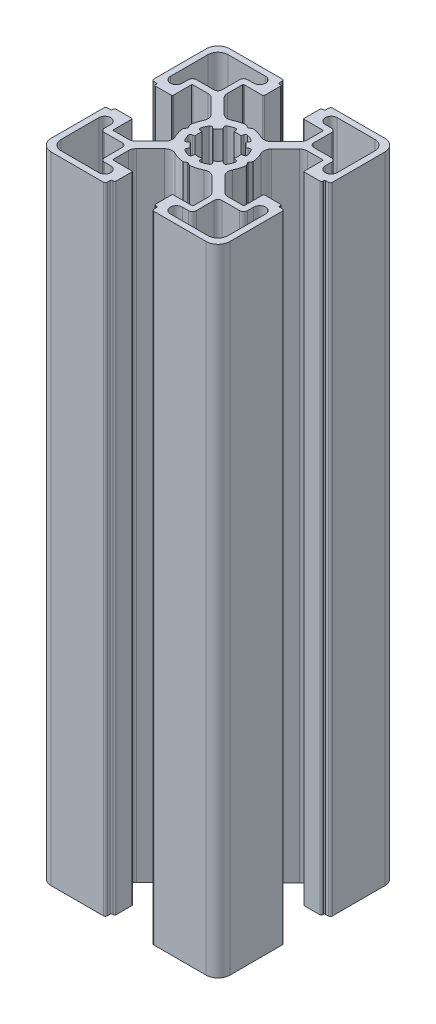
SolidWorks part; units mm, degrees
ref_plane "Front Plane" through (0, 0, 0) normal (0, 0, 1) x (1, 0, 0)
ref_plane "Top Plane" through (0, 0, 0) normal (0, 1, 0) x (1, 0, 0)
ref_plane "Right Plane" through (0, 0, 0) normal (1, 0, 0) x (0, 0, -1)
sketch "Sketch1" plane through (0, 0, 0) normal (0, 1, 0) x (1, 0, 0)
  line L106 (-18, 9.0002) -> (-18, 10.55)
  line L107 (-21, 18.5) -> (-21, 9.0002)
  line L108 (-9, 21) -> (-18.5, 21)
  line L109 (-10.55, 18) -> (-9, 18)
  line L110 (0.9675, 5.4811) -> (0.8674, 4.9242)
  line L111 (2.864, 4.0985) -> (3.1913, 4.5626)
  line L112 (4.5668, 3.2081) -> (4.0897, 2.8765)
  line L113 (4.9205, 0.8878) -> (5.4897, 0.9862)
  line L114 (5.4898, -0.9862) -> (4.9205, -0.8878)
  line L115 (4.0897, -2.8765) -> (4.5668, -3.2082)
  line L116 (3.1914, -4.5627) -> (2.864, -4.0985)
  line L117 (0.8674, -4.9242) -> (0.9675, -5.4811)
  line L118 (-0.9675, -5.4811) -> (-0.8674, -4.9242)
  line L119 (-2.864, -4.0985) -> (-3.1913, -4.5626)
  line L120 (-4.5668, -3.2082) -> (-4.0897, -2.8765)
  line L121 (-4.9205, -0.8878) -> (-5.4897, -0.9862)
  line L122 (-5.4899, 0.9862) -> (-4.9205, 0.8878)
  line L123 (-4.0897, 2.8765) -> (-4.5668, 3.2081)
  line L124 (-3.1914, 4.5627) -> (-2.864, 4.0985)
  line L125 (-0.8674, 4.9242) -> (-0.9675, 5.4811)
  line L126 (-11.55, 12.55) -> (-11.55, 17)
  line L127 (-17, 11.55) -> (-12.55, 11.55)
  line L128 (-21, -9.0002) -> (-21, -18.5)
  line L129 (-18, -10.55) -> (-18, -9.0002)
  line L130 (-12.55, -11.55) -> (-17, -11.55)
  line L131 (-11.55, -17) -> (-11.55, -12.55)
  line L132 (-9, -18) -> (-10.55, -18)
  line L133 (-18.5, -21) -> (-9, -21)
  line L134 (21, 9.0002) -> (21, 18.5)
  line L135 (18, 10.55) -> (18, 9.0002)
  line L136 (12.55, 11.55) -> (17, 11.55)
  line L137 (11.55, 17) -> (11.55, 12.55)
  line L138 (9, 18) -> (10.55, 18)
  line L139 (18.5, 21) -> (9, 21)
  line L140 (17, -11.55) -> (12.55, -11.55)
  line L141 (18, -9.0002) -> (18, -10.55)
  line L142 (21, -18.5) -> (21, -9.0002)
  line L143 (9, -21) -> (18.5, -21)
  line L144 (10.55, -18) -> (9, -18)
  line L145 (11.55, -12.55) -> (11.55, -17)
  line L146 (7.5635, 5.8587) -> (11.1298, 9.425)
  line L147 (12.5048, 9.9945) -> (16.3169, 9.9945)
  line L148 (16.5169, 9.7945) -> (16.5169, 5.2)
  line L149 (16.7169, 5) -> (20.7196, 5)
  line L150 (21.0196, 5.3) -> (21.0196, 5.5)
  line L151 (21.3196, 5.8) -> (22, 5.8)
  line L152 (22.5, 6.3) -> (22.5, 19.5)
  line L153 (19.5, 22.5) -> (6.3757, 22.5)
  line L154 (5.8757, 22) -> (5.8757, 21.3)
  line L155 (5.5757, 21) -> (5.3, 21)
  line L156 (5, 20.7) -> (5, 16.6668)
  line L157 (5.2, 16.4668) -> (9.9054, 16.4668)
  line L158 (10.1054, 16.2668) -> (10.1054, 12.4716)
  line L159 (9.5196, 11.0574) -> (5.9449, 7.4827)
  line L160 (0.7548, 7.9748) -> (0.1126, 7.6069)
  line L161 (-0.1126, 7.6069) -> (-0.7547, 7.9748)
  line L162 (-5.9449, 7.4827) -> (-9.5196, 11.0574)
  line L163 (-10.1054, 12.4716) -> (-10.1054, 16.2668)
  line L164 (-9.9054, 16.4668) -> (-5.2, 16.4668)
  line L165 (-5, 16.6668) -> (-5, 20.7)
  line L166 (-5.3, 21) -> (-5.5757, 21)
  line L167 (-5.8757, 21.3) -> (-5.8757, 22)
  line L168 (-6.3757, 22.5) -> (-19.5, 22.5)
  line L169 (-22.5, 19.5) -> (-22.5, 6.3)
  line L170 (-22, 5.8) -> (-21.3196, 5.8)
  line L171 (-21.0196, 5.5) -> (-21.0196, 5.3)
  line L172 (-20.7196, 5) -> (-16.7169, 5)
  line L173 (-16.5169, 5.2) -> (-16.5169, 9.7945)
  line L174 (-16.3169, 9.9945) -> (-12.5048, 9.9945)
  line L175 (-11.1298, 9.425) -> (-7.5635, 5.8587)
  line L176 (-7.974, 0.7926) -> (-7.5401, 0.0468)
  line L177 (-7.5401, -0.0468) -> (-7.974, -0.7926)
  line L178 (-7.5635, -5.8587) -> (-11.1298, -9.425)
  line L179 (-12.5048, -9.9945) -> (-16.3169, -9.9945)
  line L180 (-16.5169, -9.7945) -> (-16.5169, -5.2)
  line L181 (-16.7169, -5) -> (-20.7196, -5)
  line L182 (-21.0196, -5.3) -> (-21.0196, -5.5)
  line L183 (-21.3196, -5.8) -> (-22, -5.8)
  line L184 (-22.5, -6.3) -> (-22.5, -19.5)
  line L185 (-19.5, -22.5) -> (-6.3757, -22.5)
  line L186 (-5.8757, -22) -> (-5.8757, -21.3)
  line L187 (-5.5757, -21) -> (-5.3, -21)
  line L188 (-5, -20.7) -> (-5, -16.6668)
  line L189 (-5.2, -16.4668) -> (-9.9054, -16.4668)
  line L190 (-10.1054, -16.2668) -> (-10.1054, -12.4716)
  line L191 (-9.5196, -11.0574) -> (-5.9449, -7.4827)
  line L192 (-0.7547, -7.9748) -> (-0.1126, -7.6069)
  line L193 (0.1126, -7.6069) -> (0.7548, -7.9748)
  line L194 (5.9449, -7.4827) -> (9.5196, -11.0574)
  line L195 (10.1054, -12.4716) -> (10.1054, -16.2668)
  line L196 (9.9054, -16.4668) -> (5.2, -16.4668)
  line L197 (5, -16.6668) -> (5, -20.7)
  line L198 (5.3, -21) -> (5.5757, -21)
  line L199 (5.8757, -21.3) -> (5.8757, -22)
  line L200 (6.3757, -22.5) -> (19.5, -22.5)
  line L201 (22.5, -19.5) -> (22.5, -6.3)
  line L202 (22, -5.8) -> (21.3196, -5.8)
  line L203 (21.0196, -5.5) -> (21.0196, -5.3)
  line L204 (20.7196, -5) -> (16.7169, -5)
  line L205 (16.5169, -5.2) -> (16.5169, -9.7945)
  line L206 (16.3169, -9.9945) -> (12.5048, -9.9945)
  line L207 (11.1298, -9.425) -> (7.5635, -5.8587)
  line L208 (7.974, -0.7926) -> (7.5401, -0.0468)
  line L209 (7.5401, 0.0468) -> (7.974, 0.7926)
  arc A140 (-17, 11.55) -> (-18, 10.55) centre (-17, 10.55) ccw
  arc A141 (-21, 9.0002) -> (-18, 9.0002) centre (-19.5, 9.0002) ccw
  arc A142 (-18.5, 21) -> (-21, 18.5) centre (-18.5, 18.5) ccw
  arc A143 (-9, 18) -> (-9, 21) centre (-9, 19.5) ccw
  arc A144 (-10.55, 18) -> (-11.55, 17) centre (-10.55, 17) ccw
  arc A145 (-12.55, 11.55) -> (-11.55, 12.55) centre (-12.55, 12.55) ccw
  arc A146 (-21, -18.5) -> (-18.5, -21) centre (-18.5, -18.5) ccw
  arc A147 (-18, -9.0002) -> (-21, -9.0002) centre (-19.5, -9.0002) ccw
  arc A148 (-18, -10.55) -> (-17, -11.55) centre (-17, -10.55) ccw
  arc A149 (-11.55, -12.55) -> (-12.55, -11.55) centre (-12.55, -12.55) ccw
  arc A150 (-11.55, -17) -> (-10.55, -18) centre (-10.55, -17) ccw
  arc A151 (-9, -21) -> (-9, -18) centre (-9, -19.5) ccw
  arc A152 (0.8674, 4.9242) -> (-0.8674, 4.9242) centre (0, 0) ccw
  arc A153 (1.5951, 5.8941) -> (0.9675, 5.4811) centre (1.4627, 5.4119) ccw
  arc A154 (3.0417, 5.301) -> (1.5951, 5.8941) centre (0.0235, 0) ccw
  arc A155 (3.1913, 4.5626) -> (3.0417, 5.301) centre (2.7943, 4.8665) ccw
  arc A156 (4.0897, 2.8765) -> (2.864, 4.0985) centre (0, 0) ccw
  arc A157 (5.3025, 3.0565) -> (4.5668, 3.2081) centre (4.868, 2.8091) ccw
  arc A158 (5.906, 1.6142) -> (5.3025, 3.0565) centre (0.0235, 0) ccw
  arc A159 (5.4897, 0.9862) -> (5.906, 1.6142) centre (5.4239, 1.4819) ccw
  arc A160 (4.9205, -0.8878) -> (4.9205, 0.8878) centre (0, 0) ccw
  arc A161 (5.906, -1.6142) -> (5.4898, -0.9862) centre (5.4239, -1.4819) ccw
  arc A162 (5.3025, -3.0564) -> (5.906, -1.6142) centre (0.0235, 0) ccw
  arc A163 (4.5668, -3.2082) -> (5.3025, -3.0564) centre (4.868, -2.8091) ccw
  arc A164 (2.864, -4.0985) -> (4.0897, -2.8765) centre (0, 0) ccw
  arc A165 (3.0416, -5.301) -> (3.1914, -4.5627) centre (2.7943, -4.8665) ccw
  arc A166 (1.5951, -5.8941) -> (3.0416, -5.301) centre (0.0235, 0) ccw
  arc A167 (0.9675, -5.4811) -> (1.5951, -5.8941) centre (1.4627, -5.4119) ccw
  arc A168 (-0.8674, -4.9242) -> (0.8674, -4.9242) centre (0, 0) ccw
  arc A169 (-1.5951, -5.8941) -> (-0.9675, -5.4811) centre (-1.4627, -5.4119) ccw
  arc A170 (-3.0416, -5.301) -> (-1.5951, -5.8941) centre (-0.0235, 0) ccw
  arc A171 (-3.1913, -4.5626) -> (-3.0416, -5.301) centre (-2.7943, -4.8665) ccw
  arc A172 (-4.0897, -2.8765) -> (-2.864, -4.0985) centre (0, 0) ccw
  arc A173 (-5.3025, -3.0565) -> (-4.5668, -3.2082) centre (-4.868, -2.8091) ccw
  arc A174 (-5.906, -1.6142) -> (-5.3025, -3.0565) centre (-0.0235, 0) ccw
  arc A175 (-5.4897, -0.9862) -> (-5.906, -1.6142) centre (-5.4239, -1.4819) ccw
  arc A176 (-4.9205, 0.8878) -> (-4.9205, -0.8878) centre (0, 0) ccw
  arc A177 (-5.906, 1.6141) -> (-5.4899, 0.9862) centre (-5.4239, 1.4818) ccw
  arc A178 (-5.3025, 3.0564) -> (-5.906, 1.6141) centre (-0.0235, 0) ccw
  arc A179 (-4.5668, 3.2081) -> (-5.3025, 3.0564) centre (-4.868, 2.8091) ccw
  arc A180 (-2.864, 4.0985) -> (-4.0897, 2.8765) centre (0, 0) ccw
  arc A181 (-3.0417, 5.301) -> (-3.1914, 4.5627) centre (-2.7943, 4.8665) ccw
  arc A182 (-1.5951, 5.8941) -> (-3.0417, 5.301) centre (-0.0235, 0) ccw
  arc A183 (-0.9675, 5.4811) -> (-1.5951, 5.8941) centre (-1.4627, 5.4119) ccw
  arc A184 (21, 18.5) -> (18.5, 21) centre (18.5, 18.5) ccw
  arc A185 (18, 9.0002) -> (21, 9.0002) centre (19.5, 9.0002) ccw
  arc A186 (18, 10.55) -> (17, 11.55) centre (17, 10.55) ccw
  arc A187 (11.55, 12.55) -> (12.55, 11.55) centre (12.55, 12.55) ccw
  arc A188 (11.55, 17) -> (10.55, 18) centre (10.55, 17) ccw
  arc A189 (9, 21) -> (9, 18) centre (9, 19.5) ccw
  arc A190 (12.55, -11.55) -> (11.55, -12.55) centre (12.55, -12.55) ccw
  arc A191 (17, -11.55) -> (18, -10.55) centre (17, -10.55) ccw
  arc A192 (21, -9.0002) -> (18, -9.0002) centre (19.5, -9.0002) ccw
  arc A193 (18.5, -21) -> (21, -18.5) centre (18.5, -18.5) ccw
  arc A194 (9, -18) -> (9, -21) centre (9, -19.5) ccw
  arc A195 (10.55, -18) -> (11.55, -17) centre (10.55, -17) ccw
  arc A196 (7.9999, 0.9154) -> (7.2004, 3.6119) centre (0.0496, 0.0249) ccw
  arc A197 (7.5635, 5.8587) -> (7.2004, 3.6119) centre (8.9385, 4.4837) ccw
  arc A198 (12.5048, 9.9945) -> (11.1298, 9.425) centre (12.5048, 8.05) ccw
  arc A199 (16.5169, 9.7945) -> (16.3169, 9.9945) centre (16.3169, 9.7945) ccw
  arc A200 (16.5169, 5.2) -> (16.7169, 5) centre (16.7169, 5.2) ccw
  arc A201 (20.7196, 5) -> (21.0196, 5.3) centre (20.7196, 5.3) ccw
  arc A202 (21.3196, 5.8) -> (21.0196, 5.5) centre (21.3196, 5.5) ccw
  arc A203 (22, 5.8) -> (22.5, 6.3) centre (22, 6.3) ccw
  arc A204 (22.5, 19.5) -> (19.5, 22.5) centre (19.5, 19.5) ccw
  arc A205 (6.3757, 22.5) -> (5.8757, 22) centre (6.3757, 22) ccw
  arc A206 (5.5757, 21) -> (5.8757, 21.3) centre (5.5757, 21.3) ccw
  arc A207 (5.3, 21) -> (5, 20.7) centre (5.3, 20.7) ccw
  arc A208 (5, 16.6668) -> (5.2, 16.4668) centre (5.2, 16.6668) ccw
  arc A209 (10.1054, 16.2668) -> (9.9054, 16.4668) centre (9.9054, 16.2668) ccw
  arc A210 (9.5196, 11.0574) -> (10.1054, 12.4716) centre (8.1054, 12.4716) ccw
  arc A211 (3.6665, 7.1733) -> (5.9449, 7.4827) centre (4.5855, 8.9496) ccw
  arc A212 (3.6665, 7.1733) -> (0.8753, 8.0001) centre (0.0235, 0) ccw
  arc A213 (0.8753, 8.0001) -> (0.7548, 7.9748) centre (0.8542, 7.8013) ccw
  arc A214 (0, 7.531) -> (0.1126, 7.6069) centre (-0.0489, 7.7249) ccw
  arc A215 (-0.1126, 7.6069) -> (0, 7.531) centre (0.0489, 7.7249) ccw
  arc A216 (-0.7547, 7.9748) -> (-0.8753, 8.0001) centre (-0.8542, 7.8013) ccw
  arc A217 (-0.8753, 8.0001) -> (-3.6665, 7.1733) centre (-0.0235, 0) ccw
  arc A218 (-5.9449, 7.4827) -> (-3.6665, 7.1733) centre (-4.5855, 8.9496) ccw
  arc A219 (-10.1054, 12.4716) -> (-9.5196, 11.0574) centre (-8.1054, 12.4716) ccw
  arc A220 (-9.9054, 16.4668) -> (-10.1054, 16.2668) centre (-9.9054, 16.2668) ccw
  arc A221 (-5.2, 16.4668) -> (-5, 16.6668) centre (-5.2, 16.6668) ccw
  arc A222 (-5, 20.7) -> (-5.3, 21) centre (-5.3, 20.7) ccw
  arc A223 (-5.8757, 21.3) -> (-5.5757, 21) centre (-5.5757, 21.3) ccw
  arc A224 (-5.8757, 22) -> (-6.3757, 22.5) centre (-6.3757, 22) ccw
  arc A225 (-19.5, 22.5) -> (-22.5, 19.5) centre (-19.5, 19.5) ccw
  arc A226 (-22.5, 6.3) -> (-22, 5.8) centre (-22, 6.3) ccw
  arc A227 (-21.0196, 5.5) -> (-21.3196, 5.8) centre (-21.3196, 5.5) ccw
  arc A228 (-21.0196, 5.3) -> (-20.7196, 5) centre (-20.7196, 5.3) ccw
  arc A229 (-16.7169, 5) -> (-16.5169, 5.2) centre (-16.7169, 5.2) ccw
  arc A230 (-16.3169, 9.9945) -> (-16.5169, 9.7945) centre (-16.3169, 9.7945) ccw
  arc A231 (-11.1298, 9.425) -> (-12.5048, 9.9945) centre (-12.5048, 8.05) ccw
  arc A232 (-7.2004, 3.6119) -> (-7.5635, 5.8587) centre (-8.9385, 4.4837) ccw
  arc A233 (-7.2004, 3.6119) -> (-7.9999, 0.9154) centre (-0.0496, 0.0249) ccw
  arc A234 (-7.9999, 0.9154) -> (-7.974, 0.7926) centre (-7.8011, 0.8932) ccw
  arc A235 (-7.5313, 0) -> (-7.5401, 0.0468) centre (-7.7309, -0.013) ccw
  arc A236 (-7.5401, -0.0468) -> (-7.5313, 0) centre (-7.7309, 0.013) ccw
  arc A237 (-7.974, -0.7926) -> (-7.9999, -0.9154) centre (-7.8011, -0.8932) ccw
  arc A238 (-7.9999, -0.9154) -> (-7.2004, -3.6119) centre (-0.0496, -0.0249) ccw
  arc A239 (-7.5635, -5.8587) -> (-7.2004, -3.6119) centre (-8.9385, -4.4837) ccw
  arc A240 (-12.5048, -9.9945) -> (-11.1298, -9.425) centre (-12.5048, -8.05) ccw
  arc A241 (-16.5169, -9.7945) -> (-16.3169, -9.9945) centre (-16.3169, -9.7945) ccw
  arc A242 (-16.5169, -5.2) -> (-16.7169, -5) centre (-16.7169, -5.2) ccw
  arc A243 (-20.7196, -5) -> (-21.0196, -5.3) centre (-20.7196, -5.3) ccw
  arc A244 (-21.3196, -5.8) -> (-21.0196, -5.5) centre (-21.3196, -5.5) ccw
  arc A245 (-22, -5.8) -> (-22.5, -6.3) centre (-22, -6.3) ccw
  arc A246 (-22.5, -19.5) -> (-19.5, -22.5) centre (-19.5, -19.5) ccw
  arc A247 (-6.3757, -22.5) -> (-5.8757, -22) centre (-6.3757, -22) ccw
  arc A248 (-5.5757, -21) -> (-5.8757, -21.3) centre (-5.5757, -21.3) ccw
  arc A249 (-5.3, -21) -> (-5, -20.7) centre (-5.3, -20.7) ccw
  arc A250 (-5, -16.6668) -> (-5.2, -16.4668) centre (-5.2, -16.6668) ccw
  arc A251 (-10.1054, -16.2668) -> (-9.9054, -16.4668) centre (-9.9054, -16.2668) ccw
  arc A252 (-9.5196, -11.0574) -> (-10.1054, -12.4716) centre (-8.1054, -12.4716) ccw
  arc A253 (-3.6665, -7.1733) -> (-5.9449, -7.4827) centre (-4.5855, -8.9496) ccw
  arc A254 (-3.6665, -7.1733) -> (-0.8753, -8.0001) centre (-0.0235, 0) ccw
  arc A255 (-0.8753, -8.0001) -> (-0.7547, -7.9748) centre (-0.8542, -7.8013) ccw
  arc A256 (0, -7.531) -> (-0.1126, -7.6069) centre (0.0489, -7.7249) ccw
  arc A257 (0.1126, -7.6069) -> (0, -7.531) centre (-0.0489, -7.7249) ccw
  arc A258 (0.7548, -7.9748) -> (0.8753, -8.0001) centre (0.8542, -7.8012) ccw
  arc A259 (0.8753, -8.0001) -> (3.6665, -7.1733) centre (0.0235, 0) ccw
  arc A260 (5.9449, -7.4827) -> (3.6665, -7.1733) centre (4.5855, -8.9496) ccw
  arc A261 (10.1054, -12.4716) -> (9.5196, -11.0574) centre (8.1054, -12.4716) ccw
  arc A262 (9.9054, -16.4668) -> (10.1054, -16.2668) centre (9.9054, -16.2668) ccw
  arc A263 (5.2, -16.4668) -> (5, -16.6668) centre (5.2, -16.6668) ccw
  arc A264 (5, -20.7) -> (5.3, -21) centre (5.3, -20.7) ccw
  arc A265 (5.8757, -21.3) -> (5.5757, -21) centre (5.5757, -21.3) ccw
  arc A266 (5.8757, -22) -> (6.3757, -22.5) centre (6.3757, -22) ccw
  arc A267 (19.5, -22.5) -> (22.5, -19.5) centre (19.5, -19.5) ccw
  arc A268 (22.5, -6.3) -> (22, -5.8) centre (22, -6.3) ccw
  arc A269 (21.0196, -5.5) -> (21.3196, -5.8) centre (21.3196, -5.5) ccw
  arc A270 (21.0196, -5.3) -> (20.7196, -5) centre (20.7196, -5.3) ccw
  arc A271 (16.7169, -5) -> (16.5169, -5.2) centre (16.7169, -5.2) ccw
  arc A272 (16.3169, -9.9945) -> (16.5169, -9.7945) centre (16.3169, -9.7945) ccw
  arc A273 (11.1298, -9.425) -> (12.5048, -9.9945) centre (12.5048, -8.05) ccw
  arc A274 (7.2004, -3.6119) -> (7.5635, -5.8587) centre (8.9385, -4.4837) ccw
  arc A275 (7.2004, -3.6119) -> (7.9999, -0.9154) centre (0.0496, -0.0249) ccw
  arc A276 (7.9999, -0.9154) -> (7.974, -0.7926) centre (7.8011, -0.8932) ccw
  arc A277 (7.5313, 0) -> (7.5401, -0.0468) centre (7.7309, 0.013) ccw
  arc A278 (7.5401, 0.0468) -> (7.5313, 0) centre (7.7309, -0.013) ccw
  arc A279 (7.974, 0.7926) -> (7.9999, 0.9154) centre (7.8011, 0.8932) ccw
extrude "Boss-Extrude1" add sketch "Sketch1" along normal blind 160
